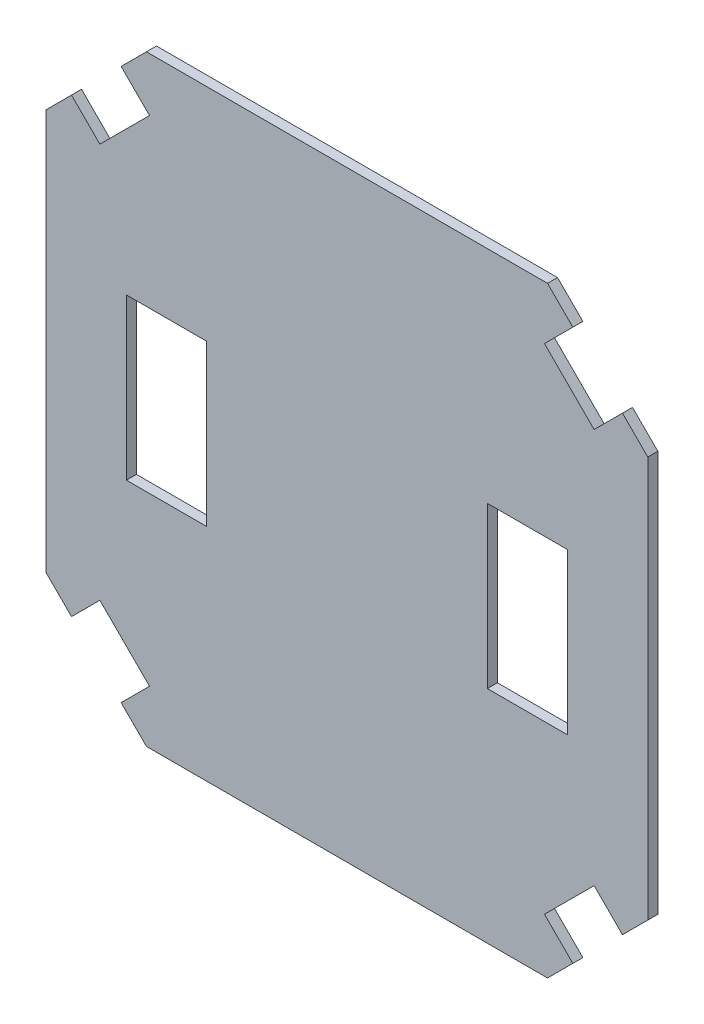
SolidWorks part; units mm, degrees
ref_plane "Plan de face" through (0, 0, 0) normal (0, 0, 1) x (1, 0, 0)
ref_plane "Plan de dessus" through (0, 0, 0) normal (0, 1, 0) x (1, 0, 0)
ref_plane "Plan de droite" through (0, 0, 0) normal (1, 0, 0) x (0, 0, -1)
sketch "Esquisse1" plane through (0, 0, 0) normal (0, 0, 1) x (1, 0, 0)
  line L0 (100, 150) -> (150, 100)
  line L1 (150, -150) -> (-150, -150)
  line L2 (150, -150) -> (150, 150)
  line L3 (150, 150) -> (-150, 150)
  line L4 (-150, -150) -> (-150, 150)
  line L5 (150, -150) -> (-150, 150) construction
  line L6 (150, 150) -> (-150, -150) construction
  line L7 (0, 237.159) -> (0, -197.6632) construction
  line L8 (-230.3021, 0) -> (257.9193, 0) construction
  line L9 (-100, 150) -> (-150, 100)
  line L10 (100, -150) -> (150, -100)
  line L11 (-100, -150) -> (-150, -100)
  line L12 (70, 40) -> (110, 40)
  line L13 (-70, -40) -> (-110, -40)
  line L14 (-70, -40) -> (-70, 40)
  line L15 (-70, 40) -> (-110, 40)
  line L16 (-110, -40) -> (-110, 40)
  line L17 (-70, -40) -> (-110, 40) construction
  line L18 (-70, 40) -> (-110, -40) construction
  line L19 (110, -40) -> (110, 40)
  line L20 (70, -40) -> (110, -40)
  line L21 (70, -40) -> (70, 40)
  line L22 (-137.3744, 112.6256) -> (-123.2322, 98.4835)
  line L23 (-123.2322, 98.4835) -> (-98.4835, 123.2322)
  line L24 (-98.4835, 123.2322) -> (-112.6256, 137.3744)
  line L25 (137.3744, 112.6256) -> (123.2322, 98.4835)
  line L26 (123.2322, 98.4835) -> (98.4835, 123.2322)
  line L27 (98.4835, 123.2322) -> (112.6256, 137.3744)
  line L28 (-137.3744, -112.6256) -> (-123.2322, -98.4835)
  line L29 (-123.2322, -98.4835) -> (-98.4835, -123.2322)
  line L30 (-98.4835, -123.2322) -> (-112.6256, -137.3744)
  line L31 (137.3744, -112.6256) -> (123.2322, -98.4835)
  line L32 (98.4835, -123.2322) -> (112.6256, -137.3744)
  line L33 (123.2322, -98.4835) -> (98.4835, -123.2322)
  point P0 (0, 0)
  point P18 (-90, 0)
  point P31 (-110.8579, 110.8579)
  dimension "D1" = 300
  dimension "D2" = 300
  dimension "D3" = 45
  dimension "D4" = 50
  dimension "D5" = 90
  dimension "D6" = 40
  dimension "D7" = 80
  dimension "D8" = 35
  dimension "D9" = 20
extrude "Boss.-Extru.1" add sketch "Esquisse1" along normal blind 5 contours L33 L31 L10 L2 L0 L25 L26 L27 L3 L9 L24 L23 L22 L4 L11 L28 L29 L30 L1 L32 L13 L16 L15 L14 L20 L21 L12 L19
